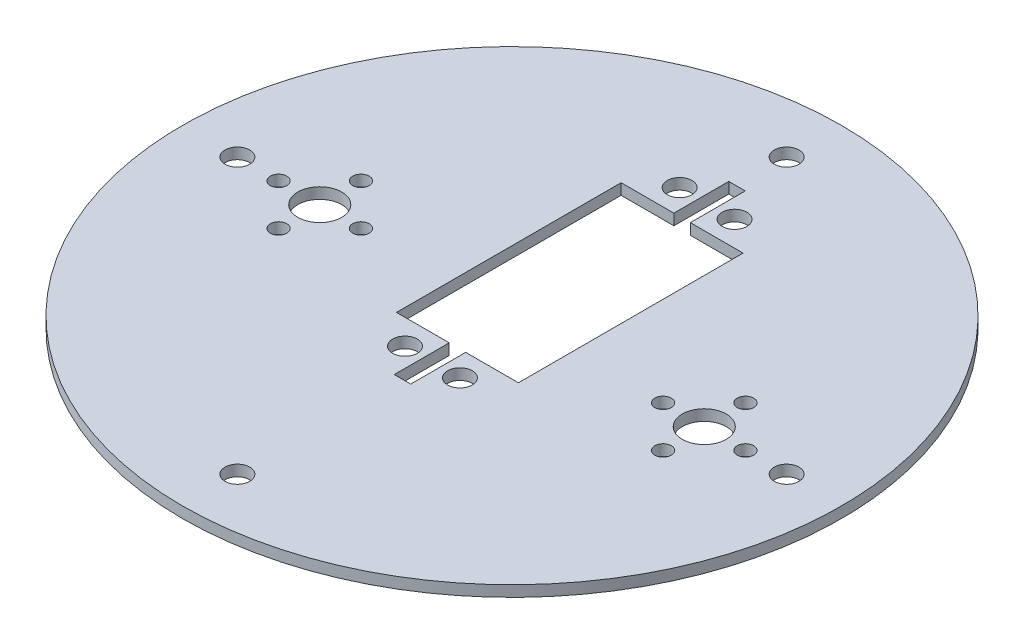
SolidWorks part; units mm, degrees
material "1060 Alloy"
ref_plane "Front Plane" through (0, 0, 0) normal (0, 0, 1) x (1, 0, 0)
ref_plane "Top Plane" through (0, 0, 0) normal (0, 1, 0) x (1, 0, 0)
ref_plane "Right Plane" through (0, 0, 0) normal (1, 0, 0) x (0, 0, -1)
sketch "Sketch1" plane through (0, 0, 0) normal (0, 1, 0) x (1, 0, 0)
  line L0 (0, 50) -> (0, -50) construction
  line L1 (-11.0324, -10) -> (11.1676, -10)
  line L2 (-11.0324, -10) -> (-11.0324, 30.9)
  line L3 (-11.0324, 30.9) -> (11.1676, 30.9)
  line L4 (11.1676, -10) -> (11.1676, 30.9)
  line L5 (-50, 0) -> (50, 0) construction
  line L6 (-11.0324, 30.9) -> (11.1676, -10) construction
  line L7 (-11.0324, -10) -> (11.1676, 30.9) construction
  line L8 (0.0676, 30.9) -> (0.0676, 40.9)
  line L9 (5.0676, -14.55) -> (-4.9324, -14.55) construction
  line L10 (5.0676, -14.55) -> (5.0676, 35.45) construction
  line L11 (5.0676, 35.45) -> (-4.9324, 35.45) construction
  line L12 (-4.9324, -14.55) -> (-4.9324, 35.45) construction
  line L13 (5.0676, -14.55) -> (-4.9324, 35.45) construction
  line L14 (5.0676, 35.45) -> (-4.9324, -14.55) construction
  line L15 (0.0676, 30.9) -> (-9.9324, 30.9)
  line L16 (0.0676, 30.9) -> (0.0676, 40.9) construction
  line L17 (0.0676, 40.9) -> (-9.9324, 40.9) construction
  line L18 (-9.9324, 30.9) -> (-9.9324, 40.9) construction
  line L19 (0.0676, 40.9) -> (10.0676, 40.9) construction
  line L20 (0.0676, 40.9) -> (0.0676, 30.9) construction
  line L21 (0.0676, 30.9) -> (10.0676, 30.9)
  line L22 (10.0676, 40.9) -> (10.0676, 30.9) construction
  line L23 (0.0676, -10) -> (-9.9324, -10)
  line L24 (0.0676, -10) -> (0.0676, -19.3445) construction
  line L25 (0.0676, -19.3445) -> (-9.9324, -19.3445) construction
  line L26 (-9.9324, -10) -> (-9.9324, -19.3445) construction
  line L27 (0.0676, -10) -> (10.0676, -10)
  line L28 (0.0676, -10) -> (0.0676, -19.3445)
  line L29 (0.0676, -19.3445) -> (10.0676, -19.3445) construction
  line L30 (10.0676, -10) -> (10.0676, -19.3445) construction
  line L31 (0.0676, -10) -> (0.0676, -19.3445)
  circle A0 centre (0, 0) radius 60
  circle A1 centre (0, 0) radius 50 construction
  circle A2 centre (0, 50) radius 2.25
  circle A3 centre (50, 0) radius 2.25
  circle A4 centre (0, -50) radius 2.25
  circle A5 centre (-50, 0) radius 2.25
  circle A6 centre (-4.9324, 35.45) radius 2.25
  circle A7 centre (5.0676, 35.45) radius 2.25
  circle A8 centre (5.0676, -14.55) radius 2.25
  circle A9 centre (-4.9324, -14.55) radius 2.25
  circle A10 centre (0, 0) radius 35 construction
  circle A11 centre (-35, 0) radius 4
  circle A12 centre (-35, 0) radius 7.5 construction
  circle A13 centre (-42.5, 0) radius 1.5
  circle A14 centre (-35, 7.5) radius 1.5
  circle A15 centre (-27.5, 0) radius 1.5
  circle A16 centre (-35, -7.5) radius 1.5
  circle A17 centre (42.5, 0) radius 1.5
  circle A18 centre (35, 0) radius 4
  circle A19 centre (35, -7.5) radius 1.5
  circle A20 centre (27.5, 0) radius 1.5
  circle A21 centre (35, 7.5) radius 1.5
  point P15 (0, 0)
  point P17 (0.0676, 10.45)
  point P56 (-35, 0)
  point P67 (0, 0)
  dimension "D1" = 120
  dimension "D2" = 100
  dimension "D3" = 4.5
  dimension "D10" = 4.5
  dimension "D16" = 70
  dimension "D17" = 8
  dimension "D18" = 15
  dimension "D19" = 3
  dimension "D5" = 22.2
  dimension "D6" = 10
  dimension "D7" = 40.9
  dimension "D8" = 10
  dimension "D9" = 50
  dimension "D13" = 10
  dimension "D14" = 10
  dimension "D15" = 10
  dimension "D11" = 2
  dimension "D12" = 2
  dimension "D4" = 4
  dimension "D20" = 4
  dimension "D21" = 2
extrude "Boss-Extrude1" add sketch "Sketch1" along normal blind 2
sketch "Sketch2" plane through (0, 0, 0) normal (0, -1, 0) x (1, 0, 0)
  line L0 (0.0676, 10) -> (0.0676, 20)
  line L1 (-11.0324, 10) -> (11.1676, 10) construction
  line L2 (0.0676, -30.9) -> (0.0676, -40.9)
  line L3 (-11.0324, -30.9) -> (11.1676, -30.9) construction
  dimension "D1" = 10
  dimension "D2" = 10
extrude "Cut-Extrude-Thin1" cut sketch "Sketch2" against normal through all thin thin type mid plane wall 3
